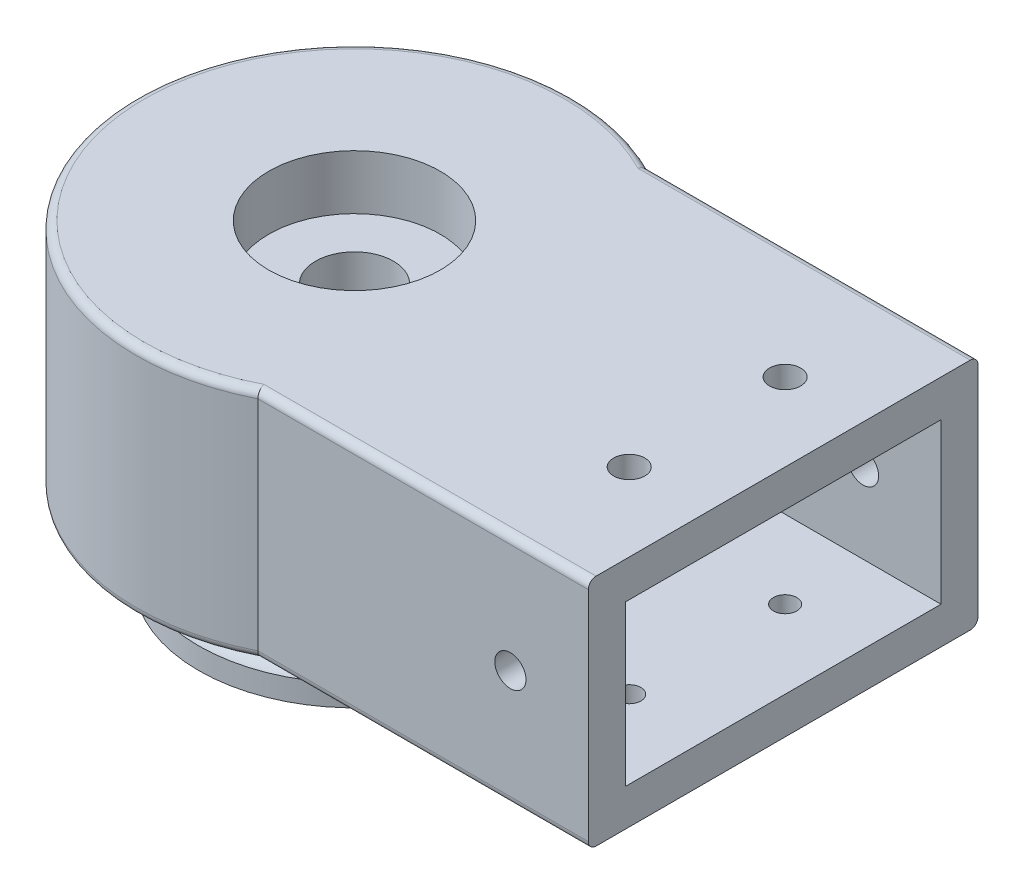
SolidWorks part; units mm, degrees
ref_plane "Front" through (0, 0, 0) normal (0, 0, 1) x (1, 0, 0)
ref_plane "Top" through (0, 0, 0) normal (0, 1, 0) x (1, 0, 0)
ref_plane "Right" through (0, 0, 0) normal (1, 0, 0) x (0, 0, -1)
sketch "Sketch1" plane through (0, 0, 0) normal (0, 0, 1) x (1, 0, 0)
  line L0 (0, 2.25) -> (0, 5)
  line L1 (0, -2.25) -> (0, -5)
  line L2 (0, -5) -> (-20, -5)
  line L3 (0, 5) -> (-20, 5)
  line L4 (-20, 5) -> (-20, -5)
  line L5 (-20, 5) -> (-20, -5) construction
  arc A0 (0, 2.25) -> (0, -2.25) centre (0, 0) ccw
revolve "Revolve2" add sketch "Sketch1" angle 360 about L5
sketch "Sketch4" plane through (0, 5, 0) normal (0, 1, 0) x (1, 0, 0)
  line L1 (-7.3905, 25) -> (50, 25)
  line L3 (-7.3905, -25) -> (50, -25)
  line L4 (50, 25) -> (50, -25)
  arc A0 (-7.3905, 25) -> (-7.3905, -25) centre (-20, 0) ccw
extrude "Boss-Extrude2" add sketch "Sketch4" along normal blind 30
sketch "Sketch5" plane through (0, -5, 0) normal (0, -1, 0) x (1, 0, 0)
  circle A0 centre (-20, 0) radius 11
extrude "Cut-Extrude1" cut sketch "Sketch5" against normal blind 7
sketch "Sketch6" plane through (0, 2, 0) normal (0, -1, 0) x (1, 0, 0)
  circle A0 centre (-20, 0) radius 5
extrude "Cut-Extrude2" cut sketch "Sketch6" against normal blind 40
sketch "Sketch7" plane through (0, 35, 0) normal (0, 1, 0) x (1, 0, 0)
  circle A0 centre (-20, 0) radius 11
extrude "Cut-Extrude3" cut sketch "Sketch7" against normal blind 7
sketch "Sketch8" plane through (50, 0, 0) normal (1, 0, 0) x (0, 0, -1)
  line L4 (-20.25, 30.25) -> (20.25, 30.25)
  line L5 (-20.25, 30.25) -> (-20.25, 9.75)
  line L6 (-20.25, 9.75) -> (20.25, 9.75)
  line L7 (20.25, 30.25) -> (20.25, 9.75)
  point P6 (0, 20)
extrude "Cut-Extrude4" cut sketch "Sketch8" against normal blind 45
sketch "Sketch9" plane through (0, 35, 0) normal (0, 1, 0) x (1, 0, 0)
  line L0 (50, 25) -> (35, 25)
  line L1 (50, 25) -> (-7.3905, 25) construction
  line L2 (35, 25) -> (35, -25)
  line L3 (-7.3905, -25) -> (50, -25) construction
  line L4 (35, -25) -> (50, -25)
  line L5 (50, -25) -> (50, 25)
extrude "Cut-Extrude5" cut sketch "Sketch9" against normal blind 45
sketch "Sketch10" plane through (0, 30.25, 0) normal (0, -1, 0) x (1, 0, 0)
  circle A0 centre (25, 9.75) radius 2
  circle A1 centre (25, -10.25) radius 2
extrude "Cut-Extrude6" cut sketch "Sketch10" against normal blind 45 and the other way blind 45
sketch "Sketch11" plane through (0, 0, -20.25) normal (0, 0, 1) x (1, 0, 0)
  circle A0 centre (25, 20) radius 2
extrude "Cut-Extrude7" cut sketch "Sketch11" against normal blind 45 and the other way blind 50
fillet "Fillet1" radius 1 6 edges at (-48, 5, 0) (13.8048, 5, -25) (13.8048, 5, 25) (13.8048, 35, -25) (-48, 35, 0) (13.8048, 35, 25)
sketch "Sketch13" plane through (0, 5, 0) normal (0, -1, 0) x (1, 0, 0)
  circle A0 centre (25, 9.75) radius 2
  circle A1 centre (25, 9.75) radius 1.5
  circle A2 centre (25, -10.25) radius 2
  circle A3 centre (25, -10.25) radius 1.5
extrude "Boss-Extrude3" add sketch "Sketch13" against normal blind 4.75
sketch "Sketch14" plane through (0, 5, 0) normal (0, -1, 0) x (1, 0, 0)
  circle A0 centre (25, 9.75) radius 2.5
  circle A1 centre (25, -10.25) radius 2.5
extrude "Cut-Extrude8" cut sketch "Sketch14" against normal blind 2.2
